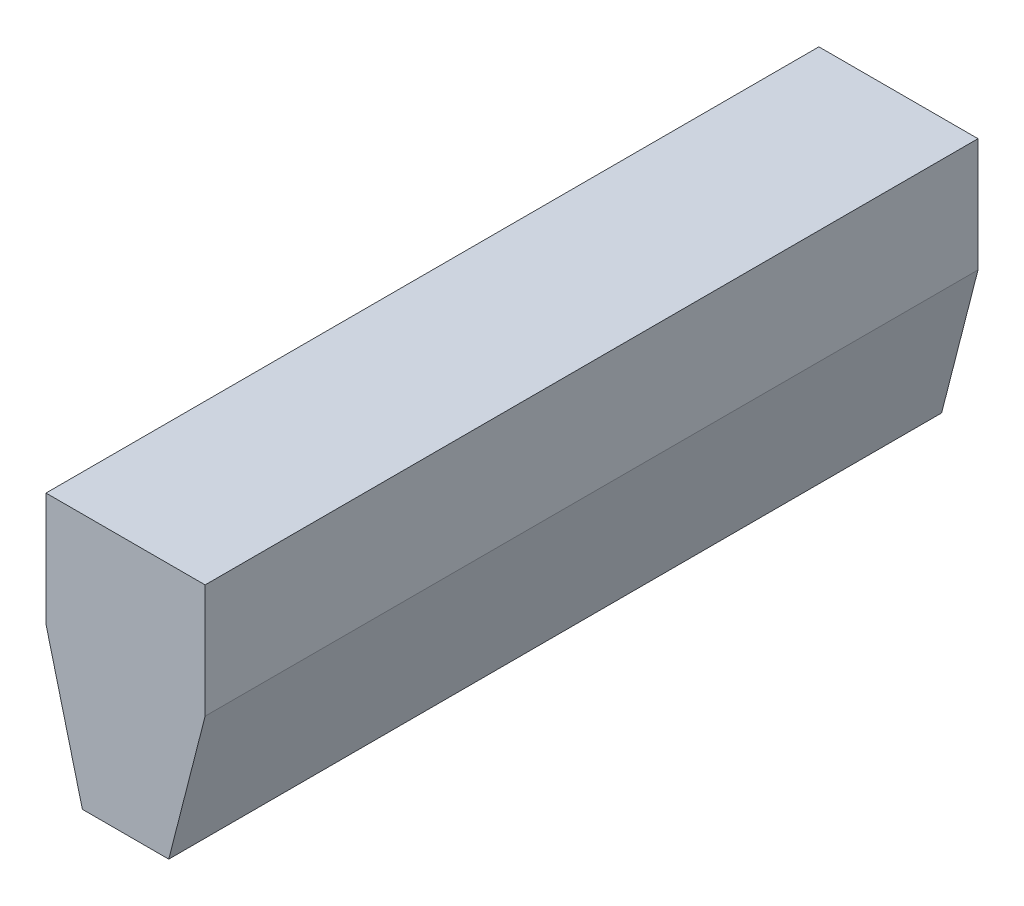
SolidWorks part; units mm, degrees
ref_plane "Front Plane" through (0, 0, 0) normal (0, 0, 1) x (1, 0, 0)
ref_plane "Top Plane" through (0, 0, 0) normal (0, 1, 0) x (1, 0, 0)
ref_plane "Right Plane" through (0, 0, 0) normal (1, 0, 0) x (0, 0, -1)
other "Configuration Table"
sketch "Sketch1" plane through (0, 0, 0) normal (0, 0, 1) x (1, 0, 0)
  line L0 (-70, 255) -> (70, 255)
  line L1 (70, 255) -> (70, 155)
  line L2 (70, 155) -> (38, 30)
  line L3 (38, 30) -> (-38, 30)
  line L4 (-38, 30) -> (-70, 155)
  line L5 (-70, 155) -> (-70, 255)
extrude "KAP_PC_govde_5mm_1" add sketch "Sketch1" against normal blind 680 from offset 20 separate body
